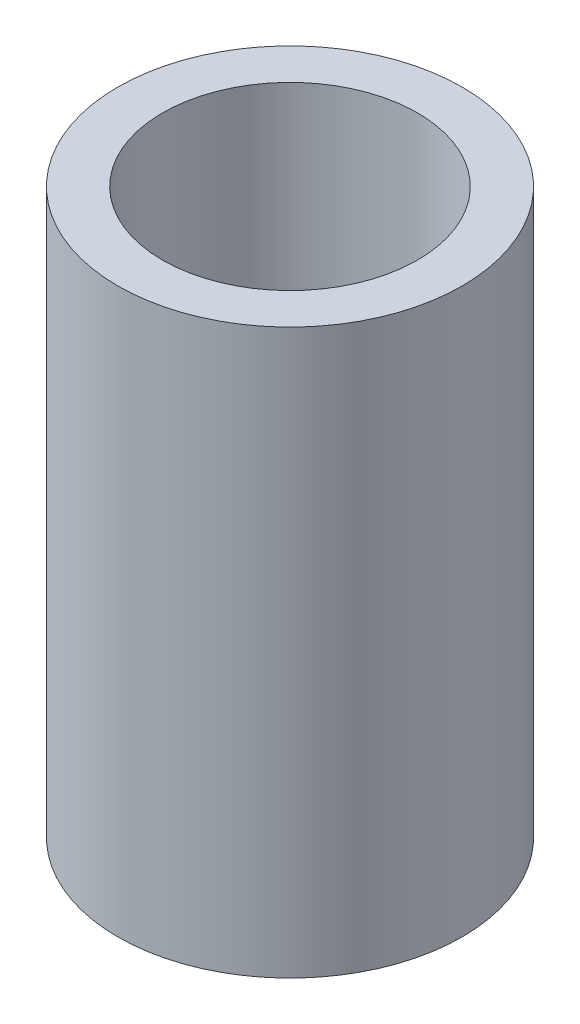
SolidWorks part; units mm, degrees
material "PVC Rigid"
ref_plane "Front Plane" through (0, 0, 0) normal (0, 0, 1) x (1, 0, 0)
ref_plane "Top Plane" through (0, 0, 0) normal (0, 1, 0) x (1, 0, 0)
ref_plane "Right Plane" through (0, 0, 0) normal (1, 0, 0) x (0, 0, -1)
sketch "Sketch1" plane through (0, 0, 0) normal (0, 1, 0) x (1, 0, 0)
  circle A0 centre (0, 0) radius 10.668
  circle A1 centre (0, 0) radius 7.8994
  dimension "D1" = 21.336
  dimension "D2" = 15.7988
  dimension "D3" = 2.7686
extrude "Boss-Extrude1" add sketch "Sketch1" along normal blind 34.925
